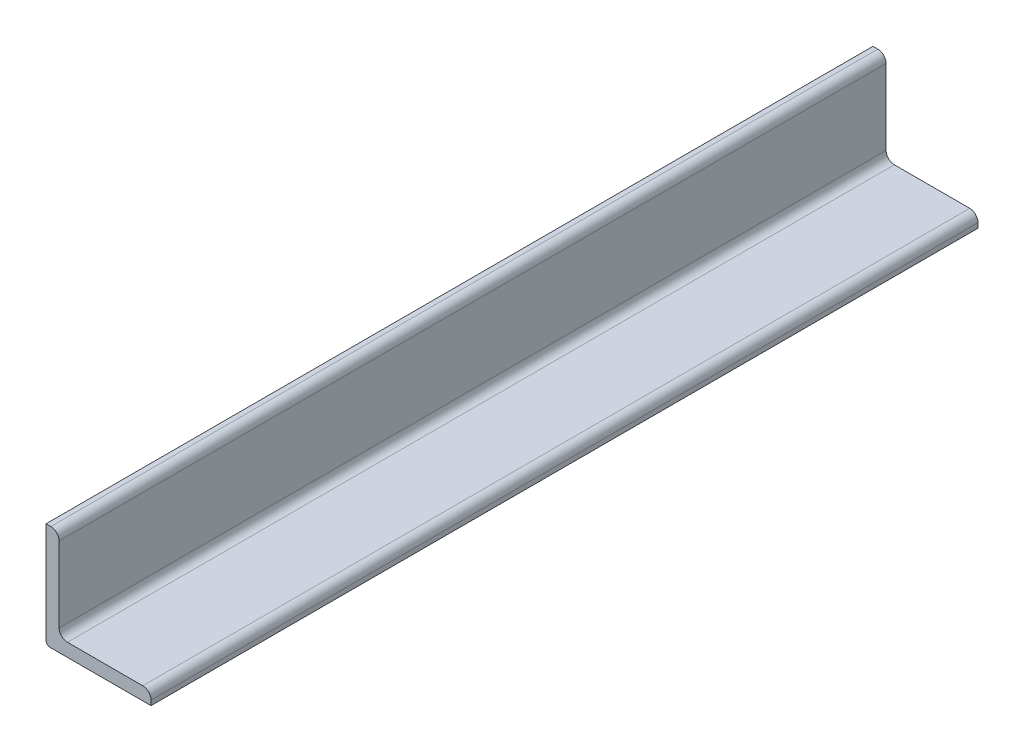
SolidWorks part; units mm, degrees
ref_plane "Front Plane" through (0, 0, 0) normal (0, 0, 1) x (1, 0, 0)
ref_plane "Top Plane" through (0, 0, 0) normal (0, 1, 0) x (1, 0, 0)
ref_plane "Right Plane" through (0, 0, 0) normal (1, 0, 0) x (0, 0, -1)
sketch "Sketch1" plane through (0, 0, 0) normal (0, 0, 1) x (1, 0, 0)
  line L0 (0, 0) -> (0, 12.7)
  line L1 (0, 12.7) -> (1.5875, 12.7)
  line L2 (1.5875, 12.7) -> (1.5875, 1.5875)
  line L3 (1.5875, 1.5875) -> (12.7, 1.5875)
  line L4 (12.7, 1.5875) -> (12.7, 0)
  line L5 (12.7, 0) -> (0, 0)
  dimension "D1" = 1.5875
  dimension "D2" = 12.7
extrude "Boss-Extrude1" add sketch "Sketch1" along normal blind 100
fillet "Fillet1" radius 0.5 1 edges at (0, 0, 50)
fillet "Fillet2" radius 1 3 edges at (1.5875, 1.5875, 50) (12.7, 1.5875, 50) (1.5875, 12.7, 50)
other "PropertyManager"
